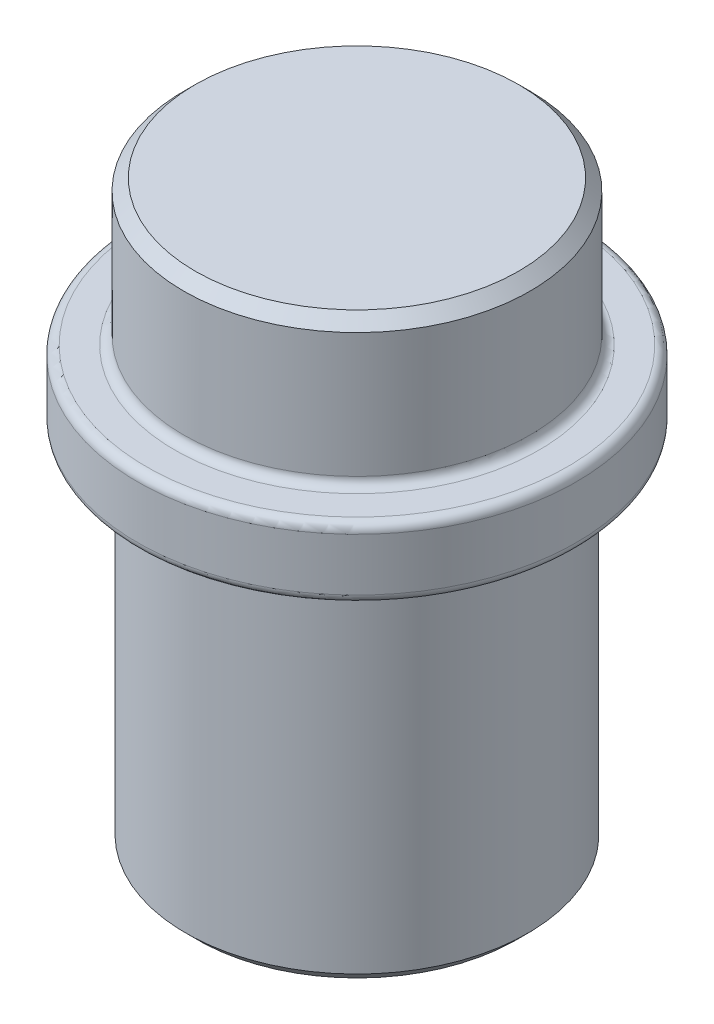
SolidWorks part; units mm, degrees
ref_plane "Front Plane" through (0, 0, 0) normal (0, 0, 1) x (1, 0, 0)
ref_plane "Top Plane" through (0, 0, 0) normal (0, 1, 0) x (1, 0, 0)
ref_plane "Right Plane" through (0, 0, 0) normal (1, 0, 0) x (0, 0, -1)
sketch "Sk_kingpin_section" plane through (0, 0, 0) normal (0, 0, 1) x (1, 0, 0)
  line L0 (0, 54.2544) -> (5.9944, 52.6491)
  line L1 (5.9944, 52.6491) -> (5.9944, 45.1282)
  line L2 (5.9944, 45.1282) -> (6.4948, 44.6278)
  line L3 (6.4948, 44.6278) -> (6.9393, 44.6278)
  line L4 (6.9393, 44.6278) -> (7.4384, 45.1282)
  line L5 (7.4384, 45.1282) -> (7.4384, 60.1218)
  line L6 (7.8194, 60.5028) -> (9.1567, 60.5028)
  line L7 (9.5377, 60.8838) -> (9.5377, 63.1698)
  line L8 (9.1567, 63.5508) -> (7.9121, 63.5508)
  line L9 (7.5311, 63.9318) -> (7.5311, 69.3496)
  line L10 (7.5311, 69.3496) -> (7.0307, 69.85)
  line L11 (7.0307, 69.85) -> (0, 69.85)
  line L12 (0, 69.85) -> (0, 54.2544)
  line L13 (0, -25.4) -> (0, 76.2) construction
  arc A0 (7.4384, 60.1218) -> (7.8194, 60.5028) centre (7.8194, 60.1218) cw
  arc A1 (9.1567, 60.5028) -> (9.5377, 60.8838) centre (9.1567, 60.8838) ccw
  arc A2 (9.5377, 63.1698) -> (9.1567, 63.5508) centre (9.1567, 63.1698) ccw
  arc A3 (7.9121, 63.5508) -> (7.5311, 63.9318) centre (7.9121, 63.9318) cw
revolve "Rev_kingpin" add sketch "Sk_kingpin_section" angle 360 about L13
ref_plane "Plane_collar_top" through (0, 63.5508, 0) normal (0, 1, 0) x (1, 0, 0)
sketch "Sk_lug" plane through (0, 63.5508, 0) normal (0, 1, 0) x (1, 0, 0)
  line L0 (-7.1933, 2.2301) -> (-7.1933, -2.2301)
  arc A0 (-7.1933, -2.2301) -> (-7.9121, -1.5545) centre (-8.1513, -2.5292) ccw
  arc A1 (-7.9121, -1.5545) -> (-7.9121, 1.5545) centre (-7.5307, 0) cw
  arc A2 (-7.9121, 1.5545) -> (-7.1933, 2.2301) centre (-8.1467, 2.5242) ccw
extrude "Ext_lug" add sketch "Sk_lug" along normal blind 2.4892
